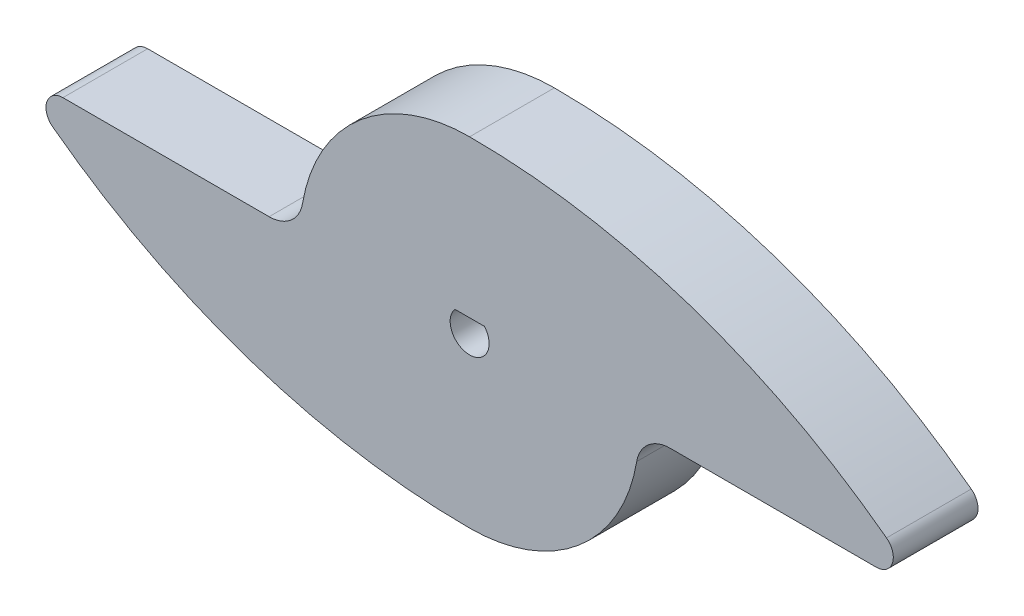
SolidWorks part; units mm, degrees
ref_plane "Front Plane" through (0, 0, 0) normal (0, 0, 1) x (1, 0, 0)
ref_plane "Top Plane" through (0, 0, 0) normal (0, 1, 0) x (1, 0, 0)
ref_plane "Right Plane" through (0, 0, 0) normal (1, 0, 0) x (0, 0, -1)
sketch "Sketch1" plane through (0, 0, 0) normal (0, 0, 1) x (1, 0, 0)
  line L0 (-1.1072, 0.9525) -> (1.1072, 0.9525)
  line L1 (0, 0) -> (-34.0777, 0) construction
  line L2 (0, 0) -> (34.0777, 0) construction
  line L3 (0, 0) -> (0, 12.7) construction
  line L4 (0, 0) -> (0, -12.7) construction
  line L5 (15.0268, 0) -> (30.48, 0)
  line L6 (-15.0268, 0) -> (-30.48, 0)
  line L7 (-31.75, 0) -> (-31.75, -6.303)
  line L8 (31.75, 0) -> (31.75, 7.1364)
  arc A0 (-1.1072, 0.9525) -> (1.1072, 0.9525) centre (0, 0) ccw
  arc A1 (0, 12.7) -> (-12.5224, 2.1167) centre (0, 0) ccw
  arc A2 (0, -12.7) -> (12.5224, -2.1167) centre (0, 0) ccw
  arc A3 (0, -12.7) -> (-31.242, -2.286) centre (0, 39.37) cw
  arc A4 (0, 12.7) -> (31.242, 2.286) centre (0, -39.37) cw
  arc A5 (31.242, 2.286) -> (30.48, 0) centre (30.48, 1.27) cw
  arc A6 (-31.242, -2.286) -> (-30.48, 0) centre (-30.48, -1.27) cw
  arc A7 (15.0268, 0) -> (12.5224, -2.1167) centre (15.0268, -2.54) ccw
  arc A8 (-15.0268, 0) -> (-12.5224, 2.1167) centre (-15.0268, 2.54) ccw
  point P24 (12.7, 0)
  point P27 (-12.7, 0)
  dimension "D1" = 2.921
  dimension "D7" = 1.27
  dimension "D8" = 2.54
  dimension "D2" = 0.9525
  dimension "D3" = 31.75
  dimension "D4" = 31.75
  dimension "D5" = 12.7
  dimension "D6" = 12.7
extrude "Boss-Extrude1" add sketch "Sketch1" along normal blind 6.35 contours A6 A3 A2 L5 A5 A4 A1 L6 A0 L0
sketch "Sketch2" plane through (0, 0, 6.35) normal (0, 0, 1) x (1, 0, 0)
  line L0 (-1.1072, 0.9525) -> (1.1072, 0.9525) construction
  line L1 (-1.1072, 0.9525) -> (1.1072, 0.9525)
  circle A0 centre (0, 0) radius 3.175
  arc A1 (-1.1072, 0.9525) -> (1.1072, 0.9525) centre (0, 0) ccw construction
  arc A2 (-1.1072, 0.9525) -> (1.1072, 0.9525) centre (0, 0) ccw
  dimension "D1" = 6.35
extrude "Boss-Extrude2" add sketch "Sketch2" against normal blind 11.1125
equation "\"D2@Sketch1\"=.095 - \"D1@Sketch1\"/2"
equation "\"D4@Sketch1\"=\"D3@Sketch1\""
